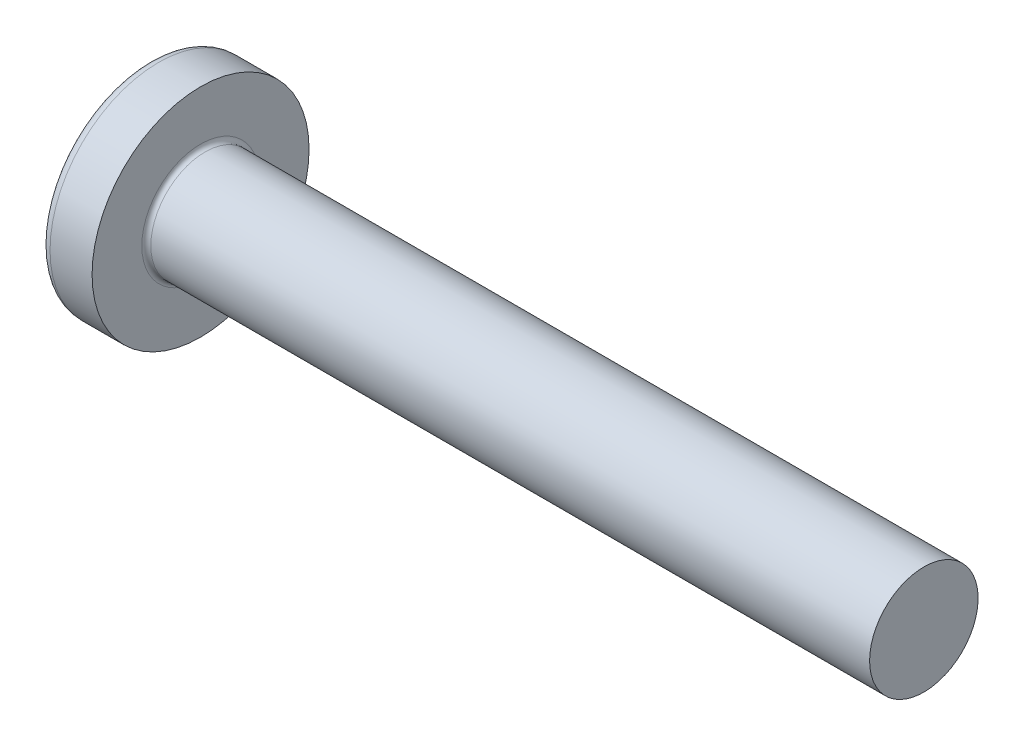
SolidWorks part; units mm, degrees
ref_plane "Plane1" through (0, 0, 0) normal (0, 0, 1) x (1, 0, 0)
ref_plane "Plane2" through (0, 0, 0) normal (0, 1, 0) x (1, 0, 0)
ref_plane "Plane3" through (0, 0, 0) normal (1, 0, 0) x (0, 0, -1)
sketch "BodySke" plane through (0, 0, 0) normal (0, 0, 1) x (1, 0, 0)
  line L0 (4.6, 3) -> (4.6, 6)
  line L1 (5.1, 6.35) -> (5.1, -3.175) construction
  line L2 (-25.4, 0) -> (127, 0) construction
  line L3 (44.6, 0) -> (0, 0)
  line L4 (4.6, 3) -> (44.6, 3)
  line L5 (44.6, 3) -> (44.6, 0)
  line L6 (2.2747, 6) -> (4.6, 6)
  line L8 (4.6, 6.35) -> (4.6, -3.175) construction
  arc A0 (1.8337, 5.7717) -> (0, 0) centre (10, 0) ccw
  arc A2 (1.8337, 5.7717) -> (2.2747, 6) centre (2.2747, 5.46) cw
  dimension "Head_crown_rad" = 10
  dimension "Head_fillet_rad" = 0.54
  dimension "Length" = 40
  dimension "Head_ht" = 4.6
  dimension "Head_dia" = 12
  dimension "Advance" = 1
  dimension "Thread_nom" = 40
  dimension "Diameter" = 6
revolve "Base-Revolve" add sketch "BodySke"
cosmetic thread "ThreadCosmetic" [suppressed]
fillet "Fillet1" radius 0.25 1 edges at (4.6, 0, 3)
sketch "Sketch3" plane through (0, 0, 0) normal (1, 0, 0) x (0, 0, -1)
  line L0 (0.71, -3.35) -> (-0.71, -3.35)
  line L1 (0.71, -3.35) -> (0.71, 3.35)
  line L2 (-0.71, 3.35) -> (0.71, 3.35)
  line L3 (-0.71, 3.35) -> (-0.71, -3.35)
  dimension "Cross_dia" = 6.7
  dimension "D1" = 3.35
  dimension "Cross_width" = 1.42
  dimension "D2" = 0.71
ref_plane "Plane4" through (3.46, 0, 0) normal (1, 0, 0) x (0, 0, -1)
sketch "Sketch4" plane through (3.46, 0, 0) normal (1, 0, 0) x (0, 0, -1)
  line L0 (0.71, -1.6249) -> (-0.71, -1.6249)
  line L1 (0.71, -1.6249) -> (0.71, 1.6249)
  line L2 (-0.71, 1.6249) -> (0.71, 1.6249)
  line L3 (-0.71, 1.6249) -> (-0.71, -1.6249)
  dimension "D1" = 1.42
  dimension "D2" = 3.2498
  dimension "D3" = 0.71
  dimension "D4" = 1.6249
loft "Recess" cut profiles "Sketch3", "Sketch4"
pattern_circular "RecPat" count 2 every 90 about axis through (0, 0, 0) along (1, 0, 0) of "Recess"
sketch "RecCorSke" plane through (0, 0, 0) normal (0, 0, 1) x (1, 0, 0)
  line L0 (-3.175, 0) -> (15.875, 0) construction
  line L1 (-25.4, 0) -> (127, 0) construction
  line L2 (0, 0) -> (0, 1.5224)
  line L3 (0, 1.5224) -> (3.46, 1.2805)
  line L4 (3.46, 1.2805) -> (3.8761, 0)
  line L5 (3.8761, 0) -> (0, 0)
  dimension "Diameter" = 2.561
  dimension "Depth" = 3.46
  dimension "Draft_angle" = 4
  dimension "Bottom_angle" = 18
revolve "RecessCore" cut sketch "RecCorSke" angle 360 about L0
sketch "ThdSchSke" plane through (0, 0, 0) normal (0, 0, 1) x (1, 0, 0)
  line L0 (6.6, -2.4455) -> (6.2117, -3)
  line L1 (6.6, -2.4455) -> (6.9883, -3)
  line L2 (6.9883, -3) -> (6.9883, -3.75)
  line L3 (-3.175, 0) -> (5.1513, 0) construction
  line L5 (6.9883, -3.75) -> (6.2117, -3.75)
  line L6 (6.2117, -3.75) -> (6.2117, -3)
  dimension "Diameter" = 6
  dimension "SideAngle" = 55
  dimension "VeeAngle" = 70
  dimension "Thread_minor" = 4.891
  dimension "Overcut" = 7.5
  dimension "Start" = 6.6
revolve "ThreadSchematic" [suppressed] cut sketch "ThdSchSke" angle 360 about L3
pattern_linear "ThdSchPat" [suppressed]
equation "\"D1@Sketch3\" = \"Cross_dia@Sketch3\" / 2"
equation "\"D2@Sketch3\" = \"Cross_width@Sketch3\" / 2"
equation "\"Depth@RecCorSke\" = \"Cross_depth@Plane4\""
equation "\"D1@Sketch4\" = \"Cross_width@Sketch3\""
equation "\"D2@Sketch4\" = \"Cross_dia@Sketch3\" - 2.0 * \"Cross_depth@Plane4\" * tan(26.5  * 0.017453292)"
equation "\"D3@Sketch4\" = \"D1@Sketch4\" / 2"
equation "\"D4@Sketch4\" = \"D2@Sketch4\" / 2"
equation "\"Thread_length@ThreadCosmetic\" = ((sgn( (\"Length@BodySke\" - \"Advance@BodySke\" * 2.0 ) - \"Thread_nom@BodySke\" )-1)*( (\"Length@BodySke\" - \"Advance@BodySke\" * 2.0 ) - \"Thread_nom@BodySke\" ))/-2+ \"Thread_nom@BodySke\""
equation "\"Thread_minor@ThdSchSke\" = \"Thread_minor@ThreadCosmetic\""
equation "\"Diameter@ThdSchSke\" = \"Diameter@BodySke\""
equation "\"Overcut@ThdSchSke\" = \"Diameter@BodySke\" * 1.25"
equation "\"Start@ThdSchSke\" = \"Head_ht@BodySke\" + \"Length@BodySke\" - \"Thread_length@ThreadCosmetic\"  '---Non-countersunk---"
equation "\"Num_threads@ThdSchPat\" = int( \"Thread_length@ThreadCosmetic\" / \"Advance@BodySke\" + 0.999 )  + 1"
equation "\"Advance@ThdSchPat\" = \"Thread_length@ThreadCosmetic\" /  (\"Num_threads@ThdSchPat\" - 1) 'relax it"
